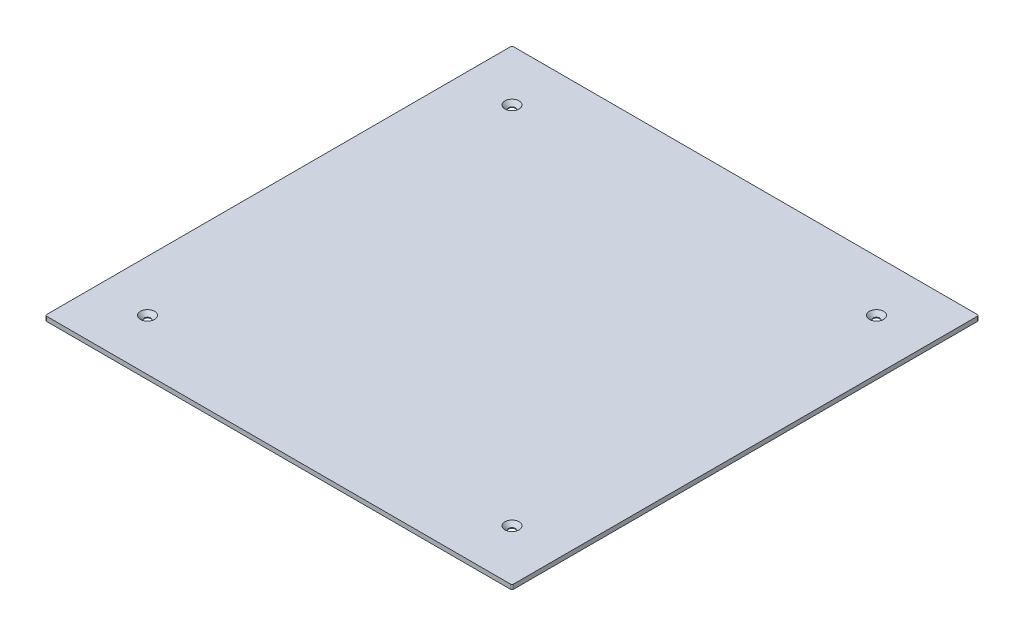
SolidWorks part; units mm, degrees
ref_plane "Płaszczyzna przednia" through (0, 0, 0) normal (0, 0, 1) x (1, 0, 0)
ref_plane "Płaszczyzna górna" through (0, 0, 0) normal (0, 1, 0) x (1, 0, 0)
ref_plane "Płaszczyzna prawa" through (0, 0, 0) normal (1, 0, 0) x (0, 0, -1)
sketch "Szkic1" plane through (0, 0, 0) normal (0, 1, 0) x (1, 0, 0)
  line L1 (0, 0) -> (310, 0)
  line L2 (0, 0) -> (0, 310)
  line L3 (0, 310) -> (310, 310)
  line L4 (310, 0) -> (310, 310)
  dimension "D1" = 310
  dimension "D2" = 310
extrude "Dodanie-wyciągnięcie1" add sketch "Szkic1" along normal blind 3
fillet "Zaokrąglenie1" radius 1 4 edges at (0, 1.5, -310) (310, 1.5, -310) (310, 1.5, 0) (0, 1.5, 0)
hole_wizard "Pogłębienie stożkowe pod M4 wkręt do części metalowych z łbem soczewkowym1" positions "Szkic2" profile "Szkic3" countersink size "M4" standard "Ansi Metric" end condition through all
sketch "Szkic2" plane through (0, 3, 0) normal (0, 1, 0) x (1, 0, 0)
  line L0 (1, 0) -> (309, 0) construction
  line L1 (0, 309) -> (0, 1) construction
  line L2 (309, 310) -> (1, 310) construction
  line L3 (310, 1) -> (310, 309) construction
  point P0 (34, 276)
  point P2 (34, 34)
  point P4 (276, 34)
  point P6 (276, 276)
  dimension "D1" = 34
  dimension "D2" = 34
  dimension "D3" = 34
  dimension "D4" = 34
  dimension "D5" = 34
  dimension "D6" = 34
  dimension "D7" = 34
  dimension "D8" = 34
sketch "Szkic3" plane through (34, 3, -276) normal (1, 0, 0) x (0, 0, 1)
  line L0 (0, 0) -> (0, 3)
  line L1 (0, 3) -> (2.15, 3)
  line L2 (2.15, 3) -> (2.15, 2.55)
  line L3 (2.15, 2.55) -> (4.7, 0)
  line L5 (4.7, 0) -> (0, 0)
  line L6 (-2.15, 2.55) -> (-4.7, 0) construction
  line L11 (0, -6.35) -> (0, 107.95) construction
  dimension "Œrednica otworu na wylot" = 4.3
  dimension "G³êbokoœæ otworu na wylot" = 3
  dimension "Œrednica zewnêtrznego pog³êbienia sto¿kowego" = 9.4
  dimension "K¹t zewnêtrznego pog³êbienia sto¿kowego" = 90
sketch "Szkic4" plane through (0, 0, 0) normal (0, -1, 0) x (-1, 0, 0)
  circle A0 centre (-34, 34) radius 3.5034
  circle A1 centre (-34, 276) radius 3.4972
  circle A2 centre (-276, 276) radius 3.5
  circle A4 centre (-276, 34) radius 3.5
  dimension "D1" = 7
  dimension "D2" = 7
split line "Linia podziałowa1"
